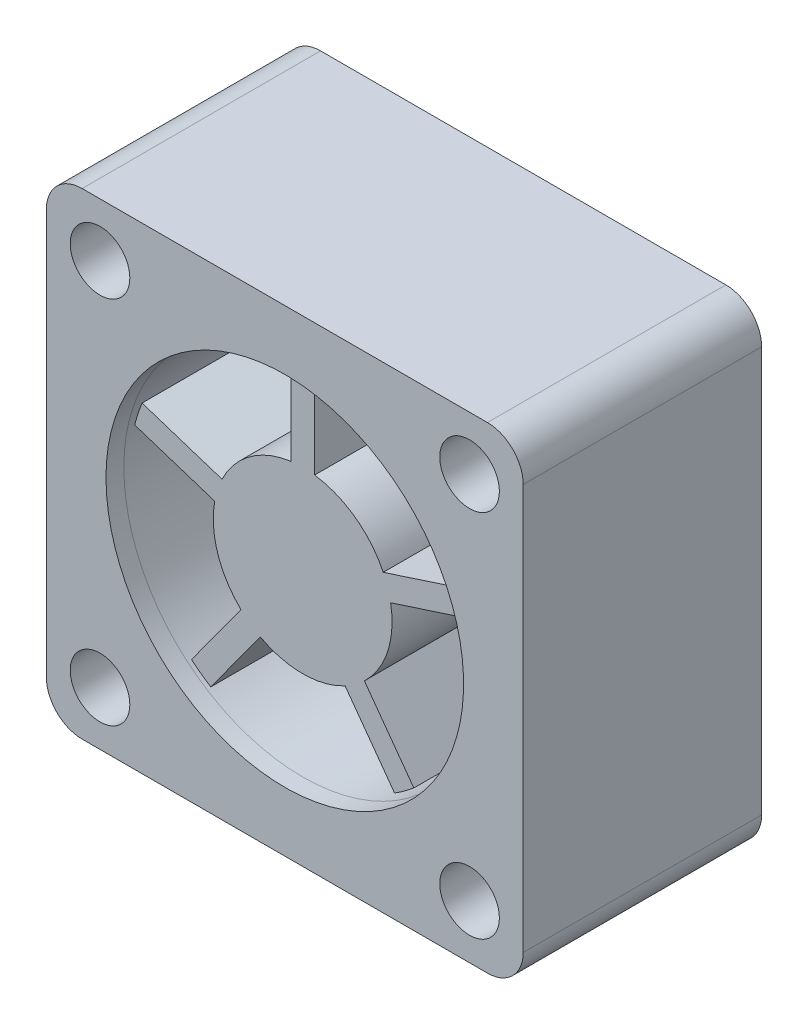
SolidWorks part; units mm, degrees
ref_plane "Ön Düzlem" through (0, 0, 0) normal (0, 0, 1) x (1, 0, 0)
ref_plane "Üst Düzlem" through (0, 0, 0) normal (0, 1, 0) x (1, 0, 0)
ref_plane "Sağ Düzlem" through (0, 0, 0) normal (1, 0, 0) x (0, 0, -1)
sketch "Sketch2" plane through (0, 0, 0) normal (0, 0, 1) x (1, 0, 0)
  line L1 (-20, -20) -> (20, -20)
  line L2 (-20, -20) -> (-20, 20)
  line L3 (-20, 20) -> (20, 20)
  line L4 (20, -20) -> (20, 20)
  line L5 (-20, -20) -> (20, 20) construction
  line L6 (-20, 20) -> (20, -20) construction
  point P0 (0, 0)
  dimension "D1" = 40
extrude "Boss-Extrude1" add sketch "Sketch2" along normal blind 20
sketch "Sketch3" plane through (0, 0, 20) normal (0, 0, 1) x (1, 0, 0)
  line L1 (-15.5, -15.5) -> (15.5, -15.5) construction
  line L2 (-15.5, -15.5) -> (-15.5, 15.5) construction
  line L3 (-15.5, 15.5) -> (15.5, 15.5) construction
  line L4 (15.5, -15.5) -> (15.5, 15.5) construction
  line L5 (-15.5, -15.5) -> (15.5, 15.5) construction
  line L6 (-15.5, 15.5) -> (15.5, -15.5) construction
  circle A0 centre (-15.5, 15.5) radius 2.5
  circle A1 centre (15.5, 15.5) radius 2.5
  circle A2 centre (15.5, -15.5) radius 2.5
  circle A3 centre (-15.5, -15.5) radius 2.5
  point P0 (0, 0)
  dimension "D2" = 5
  dimension "D1" = 31
extrude "Cut-Extrude1" cut sketch "Sketch3" against normal blind 20
fillet "Fillet1" radius 3 4 edges at (20, -20, 10) (-20, -20, 10) (-20, 20, 10) (20, 20, 10)
sketch "Sketch4" plane through (0, 0, 0) normal (0, 0, -1) x (-1, 0, 0)
  line L0 (13.9251, 5.576) -> (6.7602, 3.248)
  line L2 (-1, 14.9666) -> (-1, 7.433)
  line L4 (1, 14.9666) -> (1, 7.433)
  line L6 (14.5431, 3.6739) -> (7.3783, 1.3459)
  line L8 (9.6062, -11.5205) -> (5.178, -5.4257)
  line L10 (7.9881, -12.696) -> (3.56, -6.6012)
  line L12 (-7.9881, -12.696) -> (-3.56, -6.6012)
  line L14 (-9.6062, -11.5205) -> (-5.178, -5.4257)
  line L16 (-14.5431, 3.6739) -> (-7.3783, 1.3459)
  line L18 (-13.9251, 5.576) -> (-6.7602, 3.248)
  arc A0 (-1, 7.433) -> (-6.7602, 3.248) centre (0, 0) ccw
  arc A2 (-3.56, -6.6012) -> (3.56, -6.6012) centre (0, 0) ccw
  arc A3 (5.178, -5.4257) -> (7.3783, 1.3459) centre (0, 0) ccw
  arc A4 (6.7602, 3.248) -> (1, 7.433) centre (0, 0) ccw
  arc A9 (-7.3783, 1.3459) -> (-5.178, -5.4257) centre (0, 0) ccw
  arc A10 (-1, 14.9666) -> (-13.9251, 5.576) centre (0, 0) ccw
  arc A11 (-14.5431, 3.6739) -> (-9.6062, -11.5205) centre (0, 0) ccw
  arc A12 (-7.9881, -12.696) -> (7.9881, -12.696) centre (0, 0) ccw
  arc A13 (9.6062, -11.5205) -> (14.5431, 3.6739) centre (0, 0) ccw
  arc A14 (13.9251, 5.576) -> (1, 14.9666) centre (0, 0) ccw
  point P27 (0, 0)
  dimension "D1" = 15
  dimension "D5" = 5
extrude "Cut-Extrude4" cut sketch "Sketch4" against normal through all
sketch "Sketch5" plane through (0, 0, 20) normal (0, 0, 1) x (1, 0, 0)
  circle A0 centre (0, 0) radius 15
extrude "Cut-Extrude5" cut sketch "Sketch5" against normal blind 1.5
sketch "Sketch7" plane through (0, 0, 18.5) normal (0, 0, 1) x (1, 0, 0)
  circle A0 centre (0, 0) radius 15.025
  circle A1 centre (0, 0) radius 14.5254
  dimension "D1" = 30.05
extrude "Cut-Extrude12" cut sketch "Sketch7" against normal blind 26
